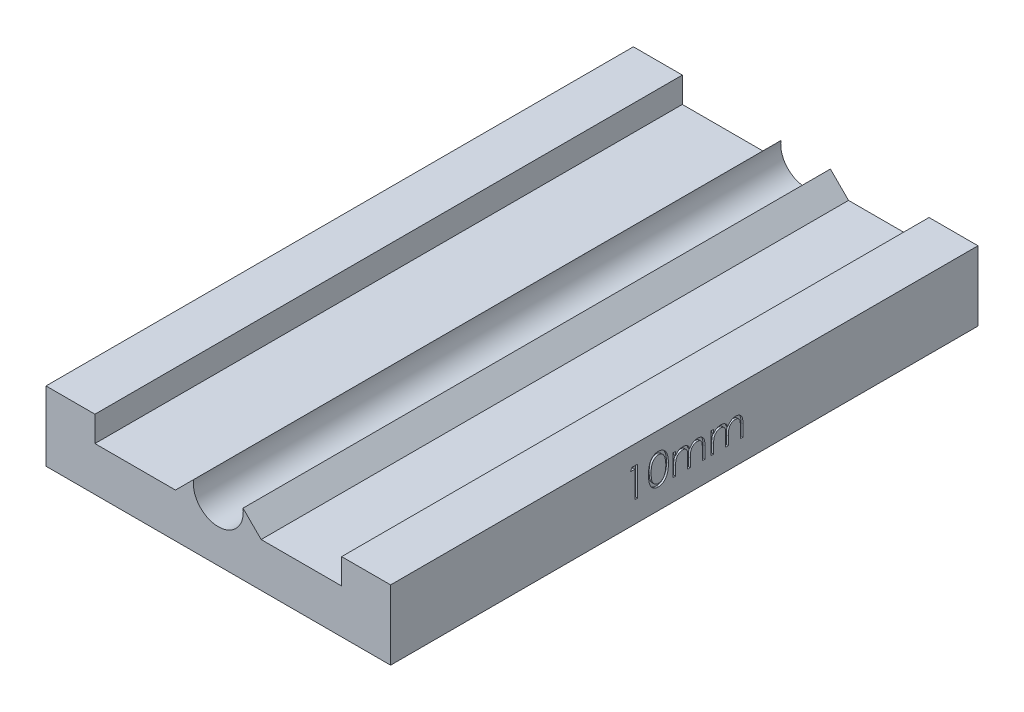
SolidWorks part; units mm, degrees
ref_plane "Front Plane" through (0, 0, 0) normal (0, 0, 1) x (1, 0, 0)
ref_plane "Top Plane" through (0, 0, 0) normal (0, 1, 0) x (1, 0, 0)
ref_plane "Right Plane" through (0, 0, 0) normal (1, 0, 0) x (0, 0, -1)
sketch "Sketch1" plane through (0, 0, 0) normal (0, 0, 1) x (1, 0, 0)
  line L0 (0, 0) -> (0, 7.2125) construction
  line L1 (0, 7.2125) -> (-10, -2.7875)
  line L2 (0, 7.2125) -> (10, -2.7875)
  line L3 (-10, -2.7875) -> (-25, -2.7875)
  line L4 (-25, -2.7875) -> (-25, 17.2125)
  line L5 (-25, 17.2125) -> (25, 17.2125)
  line L6 (25, 17.2125) -> (25, -2.7875)
  line L7 (25, -2.7875) -> (10, -2.7875)
  line L8 (-35.2, 2.2125) -> (-35.2, -12)
  line L9 (-35.2, -12) -> (35.2, -12)
  line L10 (35.2, -12) -> (35.2, 2.2125)
  line L11 (35.2, 2.2125) -> (25.2, 2.2125)
  line L12 (25.2, 2.2125) -> (25.2, -2.9875)
  line L13 (-25.2, -2.9875) -> (-8.7529, -2.9875)
  line L14 (-35.2, 2.2125) -> (-25.2, 2.2125)
  line L15 (-25.2, 2.2125) -> (-25.2, -2.9875)
  line L16 (25.2, -2.9875) -> (8.7529, -2.9875)
  line L17 (-8.7529, -2.9875) -> (-5.0495, 0.7159)
  line L18 (8.7529, -2.9875) -> (5.0495, 0.7159)
  circle A0 centre (0, 0) radius 5.1
  dimension "D12" = 10.2
  dimension "D1" = 45
  dimension "D2" = 10
  dimension "D3" = 20
  dimension "D4" = 50
  dimension "D5" = 25
  dimension "D6" = 5
  dimension "D7" = 0.2
  dimension "D8" = 0.2
  dimension "D9" = 5
  dimension "D10" = 10
  dimension "D11" = 10
  dimension "D13" = 12
  dimension "D14" = 0.2
  dimension "D15" = 0.2
extrude "Boss-Extrude1" add sketch "Sketch1" along normal blind 120 contours A0 L17 L13 L15 L14 L8 L9 L10 L11 L12 L16 L18
sketch "Sketch2" plane through (35.2, 0, 0) normal (1, 0, 0) x (0, 0, -1)
  text T0 "10mm" font "Century Gothic" height 6
extrude "Cut-Extrude1" cut sketch "Sketch2" against normal blind 0.4
